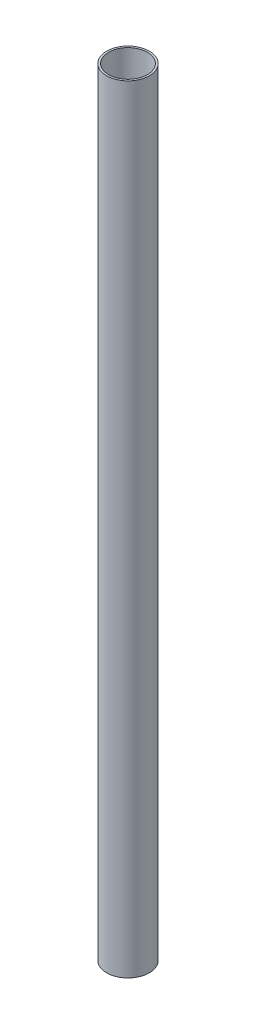
SolidWorks part; units mm, degrees
ref_plane "Plan de face" through (0, 0, 0) normal (0, 0, 1) x (1, 0, 0)
ref_plane "Plan de dessus" through (0, 0, 0) normal (0, 1, 0) x (1, 0, 0)
ref_plane "Plan de droite" through (0, 0, 0) normal (1, 0, 0) x (0, 0, -1)
sketch "Esquisse3" plane through (0, 0, 0) normal (0, 1, 0) x (1, 0, 0)
  circle A1 centre (0, 0) radius 10
  circle A2 centre (0, 0) radius 11
  dimension "D1" = 20
  dimension "D2" = 22
extrude "Boss.-Extru.1" add sketch "Esquisse3" along normal blind 400
